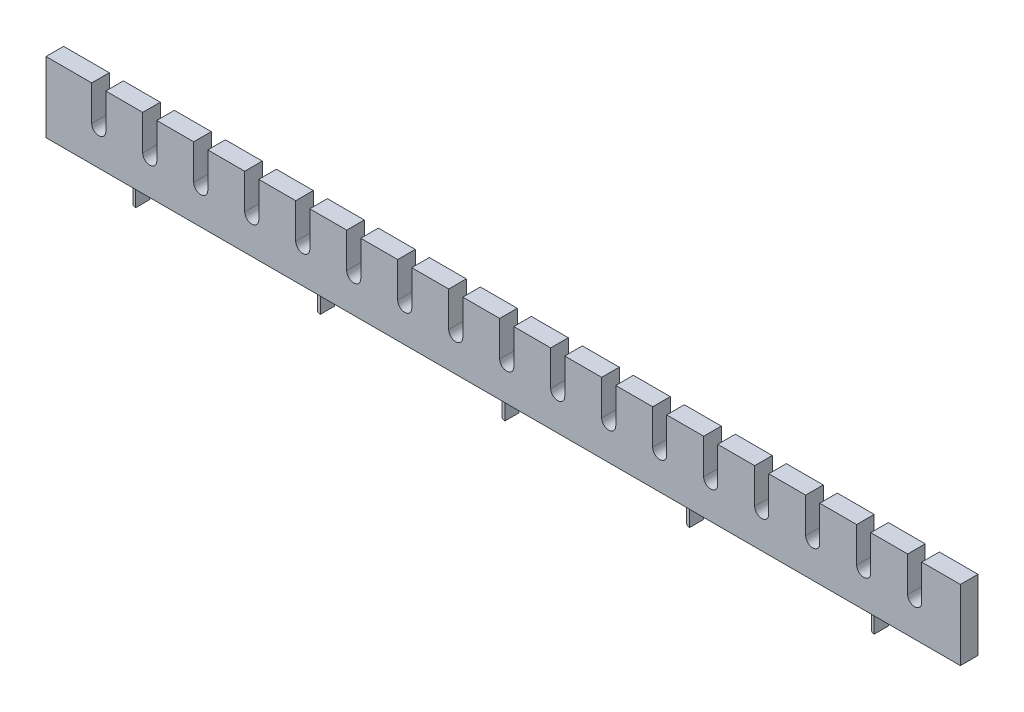
SolidWorks part; units mm, degrees
material "PPE"
ref_plane "Front Plane" through (0, 0, 0) normal (0, 0, 1) x (1, 0, 0)
ref_plane "Top Plane" through (0, 0, 0) normal (0, 1, 0) x (1, 0, 0)
ref_plane "Right Plane" through (0, 0, 0) normal (1, 0, 0) x (0, 0, -1)
sketch "Sketch1" plane through (0, 0, 0) normal (0, 1, 0) x (1, 0, 0)
  line L1 (-165.1, -3.175) -> (165.1, -3.175)
  line L2 (-165.1, -3.175) -> (-165.1, 3.175)
  line L3 (-165.1, 3.175) -> (165.1, 3.175)
  line L4 (165.1, -3.175) -> (165.1, 3.175)
  line L5 (-165.1, -3.175) -> (165.1, 3.175) construction
  line L6 (-165.1, 3.175) -> (165.1, -3.175) construction
  point P0 (0, 0)
  dimension "D1" = 6.35
  dimension "D2" = 330.2
extrude "Boss-Extrude1" add sketch "Sketch1" along normal blind 25.4 contours L2 L3 L4 L1
sketch "Sketch2" plane through (0, 0, 0) normal (0, -1, 0) x (1, 0, 0)
  line L0 (-165.1, 3.175) -> (-165.1, -3.175) construction
  line L1 (-133.35, 2.54) -> (-133.35, -2.54)
  line L2 (-66.675, 2.54) -> (-66.675, -2.54)
  line L3 (0, 2.54) -> (0, -2.54)
  line L4 (66.675, 2.54) -> (66.675, -2.54)
  line L5 (133.35, 2.54) -> (133.35, -2.54)
  arc A1 (-133.35, 2.54) -> (-133.35, -2.54) centre (-133.35, 0) ccw
  arc A8 (-66.675, 2.54) -> (-66.675, -2.54) centre (-66.675, 0) ccw
  arc A9 (0, 2.54) -> (0, -2.54) centre (0, 0) ccw
  arc A10 (66.675, 2.54) -> (66.675, -2.54) centre (66.675, 0) ccw
  arc A11 (133.35, 2.54) -> (133.35, -2.54) centre (133.35, 0) ccw
  dimension "D1" = 5.08
  dimension "D2" = 5
  dimension "D3" = 31.75
extrude "Boss-Extrude2" add sketch "Sketch2" along normal blind 6.35
sketch "Sketch3" plane through (0, 0, 3.175) normal (0, 0, 1) x (1, 0, 0)
  line L0 (-146.05, 38.1) -> (-146.05, 12.7) construction
  line L1 (-165.1, 25.4) -> (165.1, 25.4) construction
  line L2 (-143.51, 38.1) -> (-143.51, 12.7)
  line L3 (-148.59, 38.1) -> (-148.59, 12.7)
  line L4 (-127.635, 38.1) -> (-127.635, 12.7) construction
  line L5 (-125.095, 38.1) -> (-125.095, 12.7)
  line L6 (-130.175, 38.1) -> (-130.175, 12.7)
  line L7 (-109.22, 38.1) -> (-109.22, 12.7) construction
  line L8 (-106.68, 38.1) -> (-106.68, 12.7)
  line L9 (-111.76, 38.1) -> (-111.76, 12.7)
  line L10 (-90.805, 38.1) -> (-90.805, 12.7) construction
  line L11 (-88.265, 38.1) -> (-88.265, 12.7)
  line L12 (-93.345, 38.1) -> (-93.345, 12.7)
  line L13 (-72.39, 38.1) -> (-72.39, 12.7) construction
  line L14 (-69.85, 38.1) -> (-69.85, 12.7)
  line L15 (-74.93, 38.1) -> (-74.93, 12.7)
  line L16 (-53.975, 38.1) -> (-53.975, 12.7) construction
  line L17 (-51.435, 38.1) -> (-51.435, 12.7)
  line L18 (-56.515, 38.1) -> (-56.515, 12.7)
  line L19 (-35.56, 38.1) -> (-35.56, 12.7) construction
  line L20 (-33.02, 38.1) -> (-33.02, 12.7)
  line L21 (-38.1, 38.1) -> (-38.1, 12.7)
  line L22 (-17.145, 38.1) -> (-17.145, 12.7) construction
  line L23 (-14.605, 38.1) -> (-14.605, 12.7)
  line L24 (-19.685, 38.1) -> (-19.685, 12.7)
  line L25 (1.27, 38.1) -> (1.27, 12.7) construction
  line L26 (3.81, 38.1) -> (3.81, 12.7)
  line L27 (-1.27, 38.1) -> (-1.27, 12.7)
  line L28 (-165.1, 25.4) -> (-165.1, 0) construction
  line L29 (19.685, 38.1) -> (19.685, 12.7) construction
  line L30 (22.225, 38.1) -> (22.225, 12.7)
  line L31 (17.145, 38.1) -> (17.145, 12.7)
  line L32 (38.1, 38.1) -> (38.1, 12.7) construction
  line L33 (40.64, 38.1) -> (40.64, 12.7)
  line L34 (35.56, 38.1) -> (35.56, 12.7)
  line L35 (56.515, 38.1) -> (56.515, 12.7) construction
  line L36 (59.055, 38.1) -> (59.055, 12.7)
  line L37 (53.975, 38.1) -> (53.975, 12.7)
  line L38 (74.93, 38.1) -> (74.93, 12.7) construction
  line L39 (77.47, 38.1) -> (77.47, 12.7)
  line L40 (72.39, 38.1) -> (72.39, 12.7)
  line L41 (93.345, 38.1) -> (93.345, 12.7) construction
  line L42 (95.885, 38.1) -> (95.885, 12.7)
  line L43 (90.805, 38.1) -> (90.805, 12.7)
  line L44 (111.76, 38.1) -> (111.76, 12.7) construction
  line L45 (114.3, 38.1) -> (114.3, 12.7)
  line L46 (109.22, 38.1) -> (109.22, 12.7)
  line L47 (130.175, 38.1) -> (130.175, 12.7) construction
  line L48 (132.715, 38.1) -> (132.715, 12.7)
  line L49 (127.635, 38.1) -> (127.635, 12.7)
  line L50 (148.59, 38.1) -> (148.59, 12.7) construction
  line L51 (151.13, 38.1) -> (151.13, 12.7)
  line L52 (146.05, 38.1) -> (146.05, 12.7)
  arc A0 (-143.51, 38.1) -> (-148.59, 38.1) centre (-146.05, 38.1) ccw
  arc A1 (-148.59, 12.7) -> (-143.51, 12.7) centre (-146.05, 12.7) ccw
  arc A2 (-125.095, 38.1) -> (-130.175, 38.1) centre (-127.635, 38.1) ccw
  arc A3 (-130.175, 12.7) -> (-125.095, 12.7) centre (-127.635, 12.7) ccw
  arc A4 (-106.68, 38.1) -> (-111.76, 38.1) centre (-109.22, 38.1) ccw
  arc A5 (-111.76, 12.7) -> (-106.68, 12.7) centre (-109.22, 12.7) ccw
  arc A6 (-88.265, 38.1) -> (-93.345, 38.1) centre (-90.805, 38.1) ccw
  arc A7 (-93.345, 12.7) -> (-88.265, 12.7) centre (-90.805, 12.7) ccw
  arc A8 (-69.85, 38.1) -> (-74.93, 38.1) centre (-72.39, 38.1) ccw
  arc A9 (-74.93, 12.7) -> (-69.85, 12.7) centre (-72.39, 12.7) ccw
  arc A10 (-51.435, 38.1) -> (-56.515, 38.1) centre (-53.975, 38.1) ccw
  arc A11 (-56.515, 12.7) -> (-51.435, 12.7) centre (-53.975, 12.7) ccw
  arc A12 (-33.02, 38.1) -> (-38.1, 38.1) centre (-35.56, 38.1) ccw
  arc A13 (-38.1, 12.7) -> (-33.02, 12.7) centre (-35.56, 12.7) ccw
  arc A14 (-14.605, 38.1) -> (-19.685, 38.1) centre (-17.145, 38.1) ccw
  arc A15 (-19.685, 12.7) -> (-14.605, 12.7) centre (-17.145, 12.7) ccw
  arc A16 (3.81, 38.1) -> (-1.27, 38.1) centre (1.27, 38.1) ccw
  arc A17 (-1.27, 12.7) -> (3.81, 12.7) centre (1.27, 12.7) ccw
  arc A18 (22.225, 38.1) -> (17.145, 38.1) centre (19.685, 38.1) ccw
  arc A19 (17.145, 12.7) -> (22.225, 12.7) centre (19.685, 12.7) ccw
  arc A20 (40.64, 38.1) -> (35.56, 38.1) centre (38.1, 38.1) ccw
  arc A21 (35.56, 12.7) -> (40.64, 12.7) centre (38.1, 12.7) ccw
  arc A22 (59.055, 38.1) -> (53.975, 38.1) centre (56.515, 38.1) ccw
  arc A23 (53.975, 12.7) -> (59.055, 12.7) centre (56.515, 12.7) ccw
  arc A24 (77.47, 38.1) -> (72.39, 38.1) centre (74.93, 38.1) ccw
  arc A25 (72.39, 12.7) -> (77.47, 12.7) centre (74.93, 12.7) ccw
  arc A26 (95.885, 38.1) -> (90.805, 38.1) centre (93.345, 38.1) ccw
  arc A27 (90.805, 12.7) -> (95.885, 12.7) centre (93.345, 12.7) ccw
  arc A28 (114.3, 38.1) -> (109.22, 38.1) centre (111.76, 38.1) ccw
  arc A29 (109.22, 12.7) -> (114.3, 12.7) centre (111.76, 12.7) ccw
  arc A30 (132.715, 38.1) -> (127.635, 38.1) centre (130.175, 38.1) ccw
  arc A31 (127.635, 12.7) -> (132.715, 12.7) centre (130.175, 12.7) ccw
  arc A32 (151.13, 38.1) -> (146.05, 38.1) centre (148.59, 38.1) ccw
  arc A33 (146.05, 12.7) -> (151.13, 12.7) centre (148.59, 12.7) ccw
  point P4 (-146.05, 25.4)
  point P14 (-127.635, 25.4)
  point P21 (-109.22, 25.4)
  point P28 (-90.805, 25.4)
  point P35 (-72.39, 25.4)
  point P42 (-53.975, 25.4)
  point P49 (-35.56, 25.4)
  point P56 (-17.145, 25.4)
  point P63 (1.27, 25.4)
  point P70 (19.685, 25.4)
  point P77 (38.1, 25.4)
  point P84 (56.515, 25.4)
  point P91 (74.93, 25.4)
  point P98 (93.345, 25.4)
  point P105 (111.76, 25.4)
  point P112 (130.175, 25.4)
  point P119 (148.59, 25.4)
  dimension "D1" = 5.08
  dimension "D2" = 12.7
  dimension "D3" = 19.05
  dimension "D5" = 18.415
  dimension "D4" = 17
extrude "Cut-Extrude1" cut sketch "Sketch3" against normal through all
